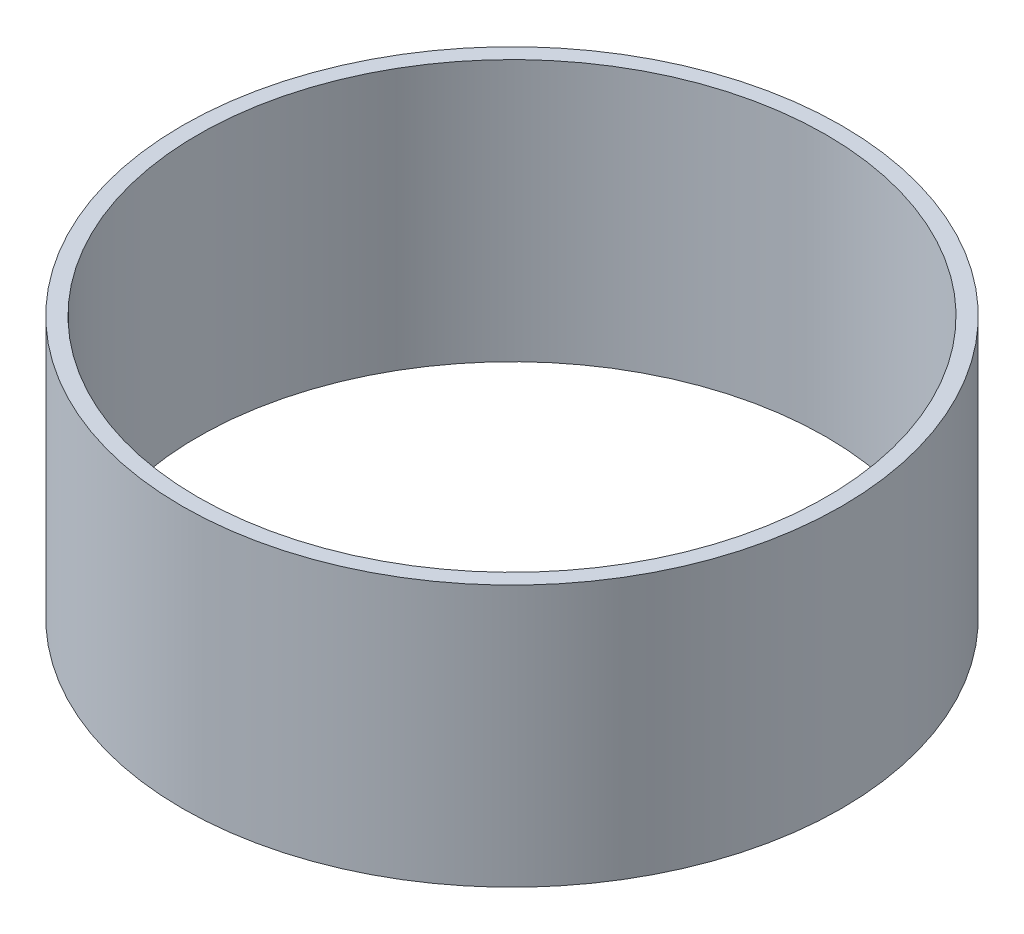
SolidWorks part; units mm, degrees
material "Медь"
ref_plane "Спереди" through (0, 0, 0) normal (0, 0, 1) x (1, 0, 0)
ref_plane "Сверху" through (0, 0, 0) normal (0, 1, 0) x (1, 0, 0)
ref_plane "Справа" through (0, 0, 0) normal (1, 0, 0) x (0, 0, -1)
sketch "Эскиз1" plane through (0, 0, 0) normal (0, 1, 0) x (1, 0, 0)
  circle A0 centre (0, 0) radius 6
  circle A1 centre (0, 0) radius 6.3
  dimension "D1" = 12
  dimension "D2" = 0.3
extrude "Бобышка-Вытянуть1" add sketch "Эскиз1" along normal blind 5
